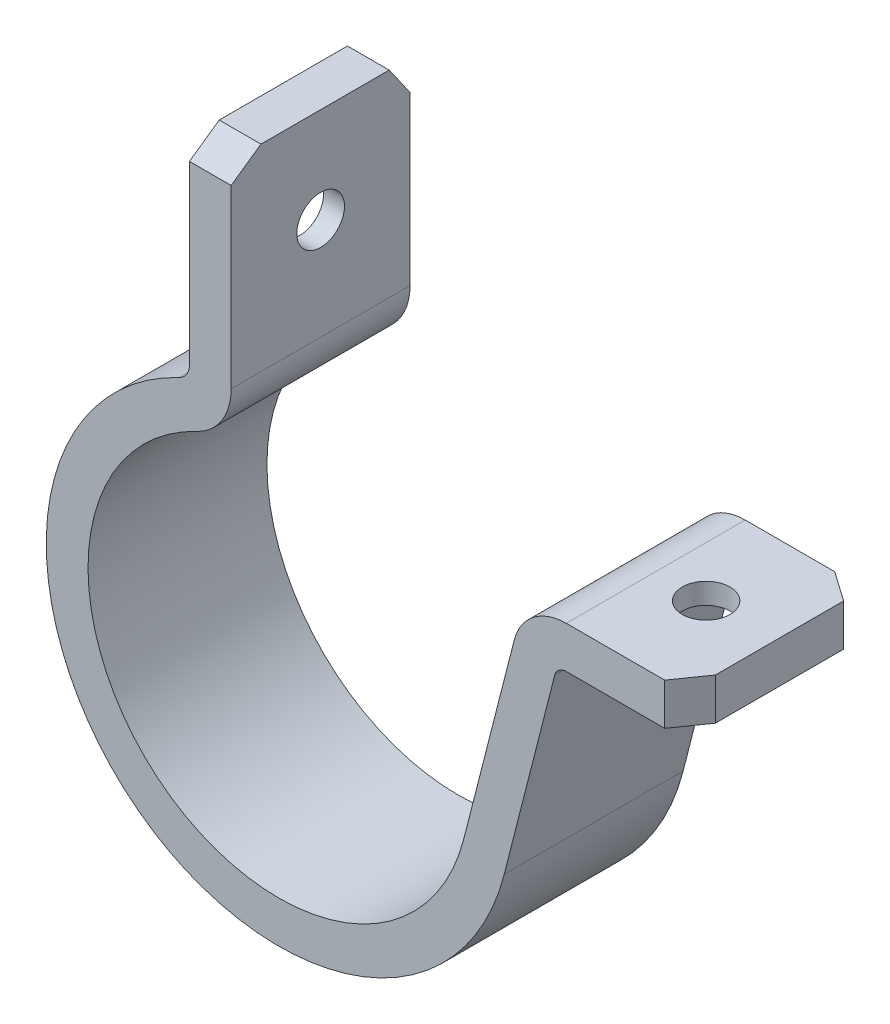
SolidWorks part; units mm, degrees
ref_plane "Front Plane" through (0, 0, 0) normal (0, 0, 1) x (1, 0, 0)
ref_plane "Top Plane" through (0, 0, 0) normal (0, 1, 0) x (1, 0, 0)
ref_plane "Right Plane" through (0, 0, 0) normal (1, 0, 0) x (0, 0, -1)
sketch "Sketch1" plane through (0, 0, 0) normal (0, 0, 1) x (1, 0, 0)
  line L1 (0, 0) -> (38.1, 0) construction
  line L2 (0, 0) -> (0, 88.9) construction
  line L3 (0, 88.9) -> (38.1, 88.9) construction
  line L4 (38.1, 0) -> (38.1, 88.9) construction
  line L5 (19.05, 88.9) -> (19.05, 0) construction
  line L6 (0, 44.45) -> (38.1, 44.45) construction
  line L8 (24.6, 0) -> (38.1, 0)
  line L14 (24.6, 0) -> (19.5024, -19.9593)
  line L15 (0, -0.5081) -> (0, 19.4919)
  line L16 (-3.5, 2) -> (-3.5, 19.4919)
  line L17 (27.3184, -3.5) -> (22.8935, -20.8254)
  line L18 (27.3184, -3.5) -> (38.1, -3.5)
  line L19 (38.1, -3.5) -> (38.1, 0)
  line L20 (0, 19.4919) -> (-3.5, 19.4919)
  arc A2 (-3.5, 2) -> (22.8935, -20.8254) centre (4, -16) ccw
  arc A4 (0, -0.5081) -> (19.5024, -19.9593) centre (4, -16) ccw
  point P92 (19.05, 44.45)
  dimension "D3" = 32
  dimension "D6" = 3.5
  dimension "D5" = 4
  dimension "D1" = 38.1
  dimension "D2" = 88.9
  dimension "D4" = 13.5
  dimension "D7" = 20
extrude "Boss-Extrude1" add sketch "Sketch1" along normal blind 15
sketch "Sketch2" plane through (0, -3.5, 0) normal (0, -1, 0) x (1, 0, 0)
  line L0 (38.1, 7.5) -> (27.3184, 7.5) construction
  line L3 (27.3184, 15) -> (27.3184, 0) construction
  line L4 (38.1, 15) -> (38.1, 0) construction
  circle A0 centre (32.3184, 7.5) radius 2
  point P2 (38.215, 7.5)
  point P3 (38.1, 7.5)
  point P4 (27.3184, 7.5)
  point P8 (30.1, 7.5)
  point P10 (0, 0)
  dimension "D1" = 4
  dimension "D2" = 5
extrude "Cut-Extrude1" cut sketch "Sketch2" against normal through all
sketch "Sketch3" plane through (-3.5, 0, 0) normal (-1, 0, 0) x (0, 0, 1)
  line L0 (7.5, 19.4919) -> (7.5, 2) construction
  line L1 (15, 19.4919) -> (0, 19.4919) construction
  line L2 (15, 2) -> (0, 2) construction
  circle A0 centre (7.5, 11.4919) radius 2
  dimension "D1" = 4
  dimension "D2" = 8
extrude "Cut-Extrude2" cut sketch "Sketch3" against normal up to surface (3.5 mm away) contours A0 up to face at (0, 9.4919, 7.5)
chamfer "Chamfer1" distance 2.5 angle 35 2 edges at (32.3184, -3.5, 5.5) (-3.5, 9.4919, 7.5)
chamfer "Chamfer2" distance 2.5 angle 35 4 edges at (38.1, -1.75, 0) (38.1, -1.75, 15) (-1.75, 19.4919, 0) (-1.75, 19.4919, 15)
fillet "Fillet1" radius 5 1 edges at (0, -0.5081, 7.5)
fillet "Fillet2" radius 1.5 1 edges at (-3.5, 2, 7.5)
fillet "Fillet3" radius 1 1 edges at (27.3184, -3.5, 7.5)
fillet "Fillet4" radius 4.5 1 edges at (24.6, 0, 7.5)
